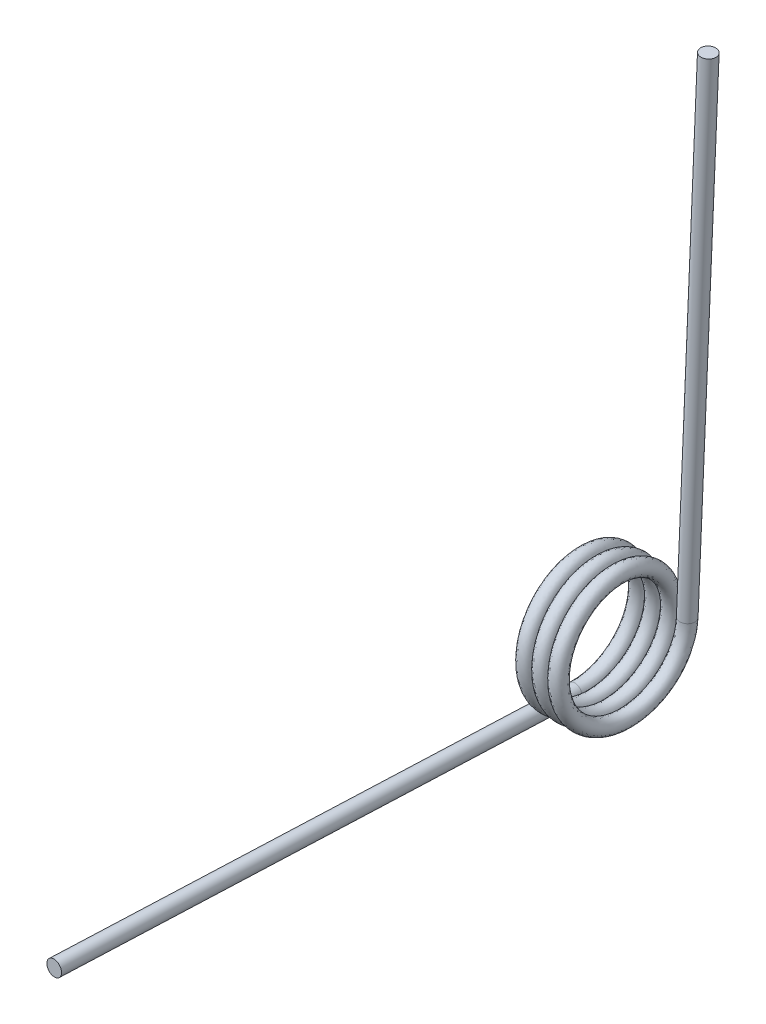
SolidWorks part; units mm, degrees
ref_plane "Front" through (0, 0, 0) normal (0, 0, 1) x (1, 0, 0)
ref_plane "Top" through (0, 0, 0) normal (0, 1, 0) x (1, 0, 0)
ref_plane "Right" through (0, 0, 0) normal (1, 0, 0) x (0, 0, -1)
sketch "Sketch1" plane through (0, 0, 0) normal (1, 0, 0) x (0, 0, -1)
  line L0 (0, 0) -> (0, -2.0066) construction
  line L1 (0, -2.0066) -> (0, -2.2987) construction
  line L2 (0, -2.2987) -> (0, -2.5908) construction
  circle A0 centre (0, 0) radius 2.0066 construction
  circle A1 centre (0, 0) radius 2.5908 construction
  circle A2 centre (0, 0) radius 2.2987
  circle A3 centre (0, -2.2987) radius 0.2921 construction
  circle A4 centre (0, 0) radius 1.651 construction
  dimension "Wire Dia" = 0.5842
  dimension "Spring OD" = 5.1816
  dimension "Max Rod OD" = 3.302
curve "Helix/Spiral1" pitch 0.6096 height 1.9812 turns 3.25
ref_plane "Plane1" through (0, -2.2987, 0) normal (0.0422, 0, -0.9991) x (0.9951, 0.0893, 0.042)
sketch "Sketch2" plane through (0, -2.2987, 0) normal (0.0422, 0, -0.9991) x (0.9951, 0.0893, 0.042)
  circle A0 centre (0, 0) radius 0.2921
  dimension "D1" = 0.5842
sweep "Sweep1" add profiles "Sketch2" path "Helix/Spiral1"
sketch "Sketch3" plane through (0, 0, 0) normal (-0.0422, 0, 0.9991) x (-0.9951, -0.0893, -0.042)
  circle A1 centre (0.2052, 2.2895) radius 0.2921
  circle A2 centre (0.2052, 2.2895) radius 0.2921
  dimension "D1" = 0
extrude "Extrude1" add sketch "Sketch3" along normal blind 19.05
sketch "Sketch4" plane through (0.0035, 0.0835, 0) normal (0.0422, 0.9991, 0) x (0.9951, -0.042, -0.0893)
  circle A1 centre (2.1767, 2.1128) radius 0.2921
  circle A2 centre (2.1767, 2.1128) radius 0.2921
  dimension "D1" = 0
extrude "Extrude2" add sketch "Sketch4" along normal blind 19.05
sketch "Sketch5" plane through (0, 0, 0) normal (1, 0, 0) x (0, 0, -1)
  circle A0 centre (0, 0) radius 1.651 construction
  circle A1 centre (0, 0) radius 1.651
equation "\"D4@Helix/Spiral1\"=\"Wire Dia@Sketch1\"+.001"
equation "\"D1@Sketch2\"=\"Wire Dia@Sketch1\""
equation "\"D1@Extrude2\"=\"Leg Length@Extrude1\""
